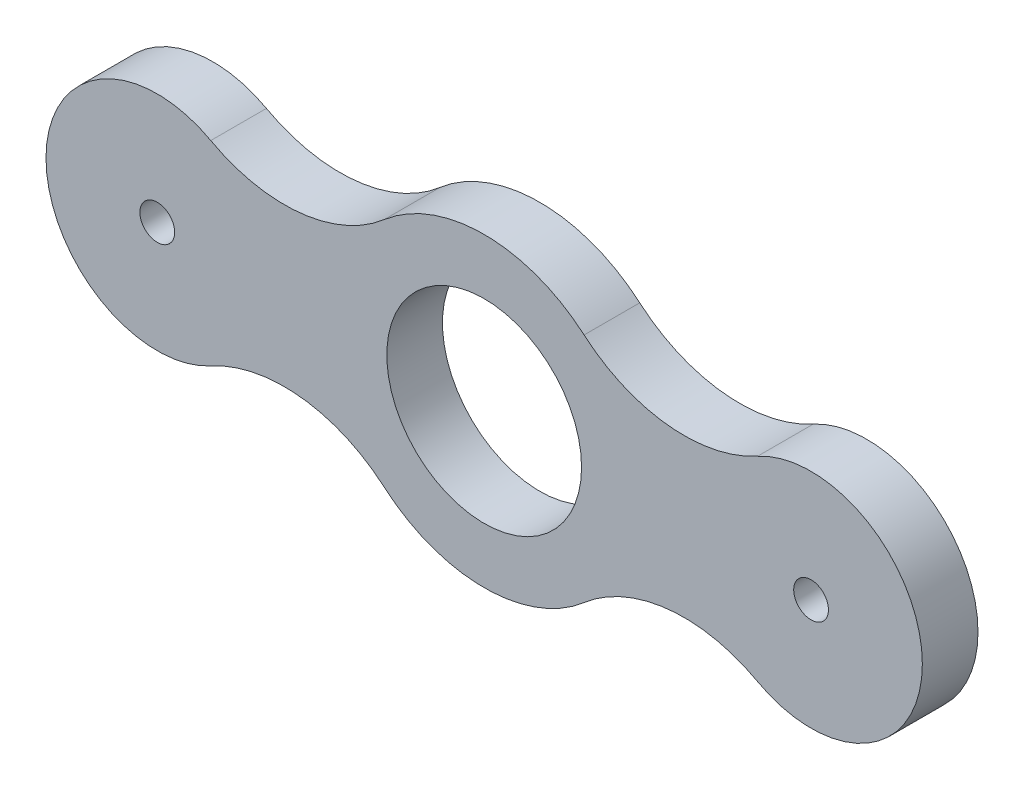
SolidWorks part; units mm, degrees
ref_plane "Front Plane" through (0, 0, 0) normal (0, 0, 1) x (1, 0, 0)
ref_plane "Top Plane" through (0, 0, 0) normal (0, 1, 0) x (1, 0, 0)
ref_plane "Right Plane" through (0, 0, 0) normal (1, 0, 0) x (0, 0, -1)
sketch "Sketch1" plane through (0, 0, 0) normal (0, 0, 1) x (1, 0, 0)
  line L0 (0, 0) -> (0, 14.047) construction
  line L1 (0, 0) -> (0, -13.0254) construction
  line L2 (0, 0) -> (-11.75, 0) construction
  line L3 (-11.75, 0) -> (-16, 0) construction
  circle A0 centre (-11.75, 0) radius 0.625
  arc A1 (-9.8273, 3.5076) -> (-9.8273, -3.5076) centre (-11.75, 0) ccw
  circle A2 centre (0, 0) radius 3.5
  arc A14 (3.5918, 4.1652) -> (-3.5918, 4.1652) centre (0, 0) ccw
  arc A15 (-9.8273, 3.5076) -> (-3.5918, 4.1652) centre (-7.1835, 8.3305) ccw
  arc A16 (-9.8273, -3.5076) -> (-3.5918, -4.1652) centre (-7.1835, -8.3305) cw
  arc A17 (3.5918, -4.1652) -> (-3.5918, -4.1652) centre (0, 0) cw
  arc A18 (9.8273, -3.5076) -> (3.5918, -4.1652) centre (7.1835, -8.3305) ccw
  arc A19 (9.8273, 3.5076) -> (9.8273, -3.5076) centre (11.75, 0) cw
  arc A20 (9.8273, 3.5076) -> (3.5918, 4.1652) centre (7.1835, 8.3305) cw
  circle A21 centre (11.75, 0) radius 0.625
  dimension "D4" = 8
  dimension "D6" = 1.25
  dimension "D9" = 5.5
  dimension "D10" = 11
  dimension "D12" = 7
  dimension "D3" = 11.75
extrude "Boss-Extrude1" add sketch "Sketch1" along normal blind 2
